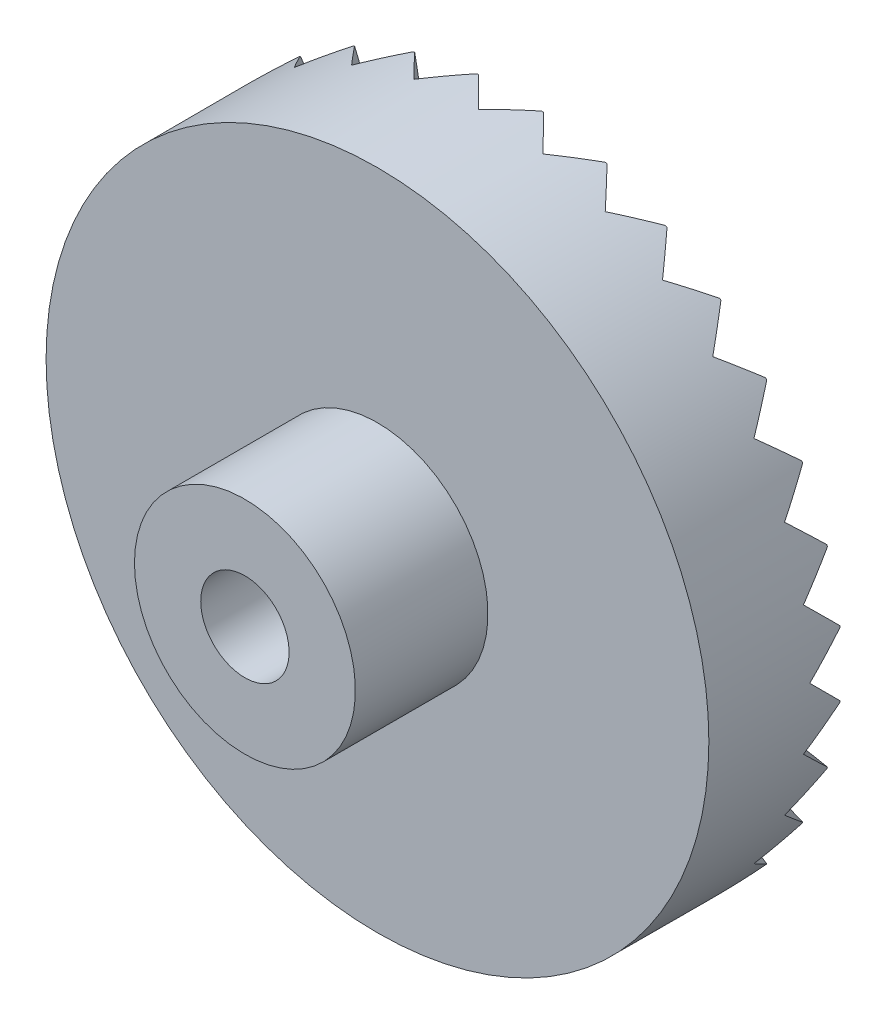
SolidWorks part; units mm, degrees
material "ABS"
ref_plane "Front Plane" through (0, 0, 0) normal (0, 0, 1) x (1, 0, 0)
ref_plane "Top Plane" through (0, 0, 0) normal (0, 1, 0) x (1, 0, 0)
ref_plane "Right Plane" through (0, 0, 0) normal (1, 0, 0) x (0, 0, -1)
sketch "Sketch1" plane through (0, 0, 0) normal (0, 1, 0) x (1, 0, 0)
  line L0 (1, 0) -> (6.5, 0)
  line L1 (6.5, 0) -> (6.5, 2)
  line L2 (6.5, 2) -> (7.5, 2)
  line L3 (7.5, 2) -> (7.5, -1)
  line L4 (7.5, -1) -> (2.5, -1)
  line L5 (2.5, -1) -> (2.5, -4)
  line L6 (2.5, -4) -> (1, -4)
  line L7 (1, -4) -> (1, 0)
  line L8 (0, 10.7101) -> (0, -13.3366) construction
  dimension "D1" = 7.5
  dimension "D2" = 3
  dimension "D3" = 1
  dimension "D4" = 1
  dimension "D5" = 3
  dimension "D6" = 1
  dimension "D7" = 2.5
revolve "Revolve1" add sketch "Sketch1" angle 360 about L8
sketch "Sketch2" plane through (0, 0, 0) normal (0, 1, 0) x (1, 0, 0)
  line L0 (0, 1.2843) -> (2.0601, 3.3444)
  line L1 (2.0601, 3.3444) -> (-2.0601, 3.3444)
  line L2 (-2.0601, 3.3444) -> (0, 1.2843)
  point P0 (0, 1.2843)
  point P2 (0, 0)
extrude "Cut-Extrude1" cut sketch "Sketch2" against normal blind 10
pattern_circular "CirPattern1" count 32 over 360 about axis through (0, 0, 0) along (0, 0, 1) of "Cut-Extrude1"
